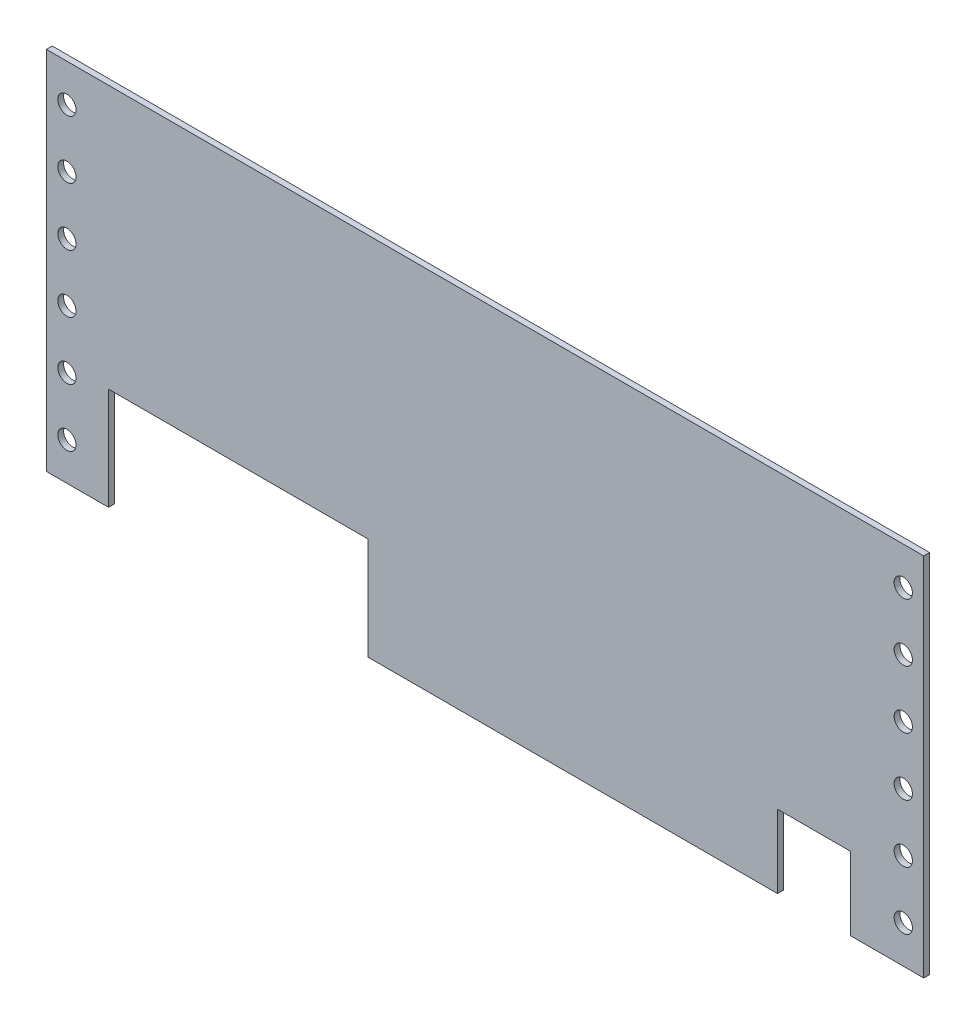
SolidWorks part; units mm, degrees
ref_plane "Front Plane" through (0, 0, 0) normal (0, 0, 1) x (1, 0, 0)
ref_plane "Top Plane" through (0, 0, 0) normal (0, 1, 0) x (1, 0, 0)
ref_plane "Right Plane" through (0, 0, 0) normal (1, 0, 0) x (0, 0, -1)
sketch "Sketch1" plane through (0, 0, 0) normal (0, 0, 1) x (1, 0, 0)
  line L1 (0, 0) -> (240, 0)
  line L2 (0, 0) -> (0, 100)
  line L3 (0, 100) -> (240, 100)
  line L4 (240, 0) -> (240, 100)
  dimension "D1" = 240
  dimension "D2" = 100
extrude "Boss-Extrude1" add sketch "Sketch1" along normal blind 1.6
sketch "Sketch2" plane through (0, 0, 1.6) normal (0, 0, 1) x (1, 0, 0)
  line L0 (0, 100) -> (0, 0) construction
  line L1 (0, 0) -> (240, 0) construction
  line L2 (240, 0) -> (240, 100) construction
  circle A0 centre (5.6, 10.3) radius 2.5
  circle A1 centre (234.4, 10.3) radius 2.5
  dimension "D1" = 5
  dimension "D2" = 5.6
  dimension "D3" = 10.3
  dimension "D4" = 5.6
extrude "Cut-Extrude1" cut sketch "Sketch2" against normal up to next
pattern_linear "LPattern1" count 6 spacing 15.88 along (0, 1, 0) of "Cut-Extrude1"
sketch "Sketch3" plane through (0, 0, 1.6) normal (0, 0, 1) x (1, 0, 0)
  line L1 (17, 28) -> (88, 28)
  line L2 (17, 28) -> (17, 0)
  line L3 (17, 0) -> (88, 0)
  line L4 (88, 28) -> (88, 0)
  line L5 (0, 100) -> (0, 0) construction
  line L6 (0, 0) -> (240, 0) construction
  point P4 (21.2292, 0)
  point P5 (20.9358, 20.1246)
  point P10 (0, 0)
  dimension "D1" = 17
  dimension "D2" = 88
  dimension "D3" = 28
extrude "Cut-Extrude2" cut sketch "Sketch3" against normal up to next
sketch "Sketch4" plane through (0, 0, 0) normal (0, 0, -1) x (-1, 0, 0)
  line L0 (-88, 0) -> (-240, 0) construction
  line L1 (-220, 0) -> (-200, 0)
  line L2 (-220, 0) -> (-220, 20)
  line L3 (-220, 20) -> (-200, 20)
  line L4 (-200, 0) -> (-200, 20)
  line L5 (-240, 0) -> (-240, 100) construction
  dimension "D1" = 20
  dimension "D2" = 20
  dimension "D3" = 20
extrude "Cut-Extrude3" cut sketch "Sketch4" against normal up to next
